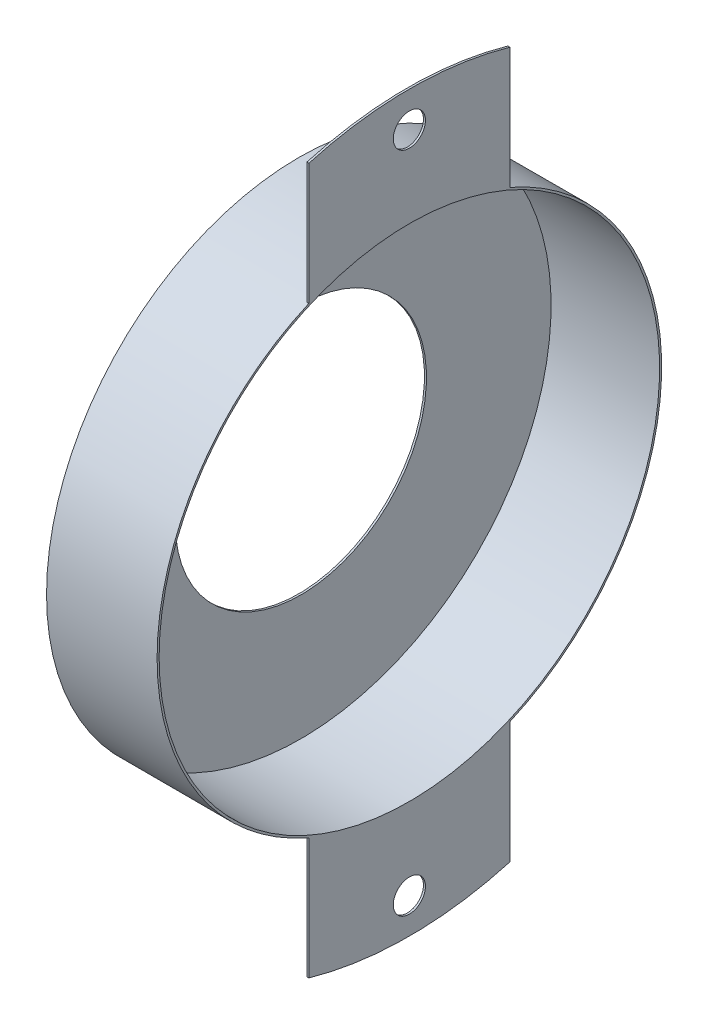
SolidWorks part; units mm, degrees
ref_plane "Ön Düzlem" through (0, 0, 0) normal (0, 0, 1) x (1, 0, 0)
ref_plane "Üst Düzlem" through (0, 0, 0) normal (0, 1, 0) x (1, 0, 0)
ref_plane "Sağ Düzlem" through (0, 0, 0) normal (1, 0, 0) x (0, 0, -1)
sketch "Sketch1" plane through (0, 0, 0) normal (0, 0, 1) x (1, 0, 0)
  line L0 (0, 0) -> (0, 25) construction
  line L1 (0, 25) -> (10.8, 25) construction
  line L2 (10.8, 25) -> (10.8, 36.5) construction
  line L3 (0, 0) -> (8.7607, 0) construction
  line L4 (0.1, 0) -> (0.1, 24.9)
  line L5 (0.1, 24.9) -> (10.9, 24.9)
  line L6 (10.9, 24.9) -> (10.9, 36.5)
  line L7 (-0.1, 0) -> (-0.1, 25.1)
  line L8 (-0.1, 25.1) -> (10.7, 25.1)
  line L9 (10.7, 25.1) -> (10.7, 36.5)
  line L10 (10.7, 36.5) -> (10.9, 36.5)
  line L11 (-0.1, 0) -> (0.1, 0)
  dimension "D1" = 25
  dimension "D2" = 10.8
  dimension "D3" = 11.5
  dimension "D4" = 0.1
  dimension "D5" = 0.1
revolve "Revolve1" add sketch "Sketch1" angle 360 about L3
sketch "Sketch2" plane through (-0.1, 0, 0) normal (-1, 0, 0) x (0, 0, 1)
  circle A0 centre (0, 0) radius 12.5
  dimension "D1" = 25
sketch "Sketch3" plane through (-0.1, 0, 0) normal (-1, 0, 0) x (0, 0, 1)
  line L0 (0, 36.5) -> (0, -36.5) construction
  line L1 (-10, 35.1034) -> (-10, -35.1034)
  line L2 (10, 35.1034) -> (10, -35.1034)
  line L3 (-10, 36.5) -> (-10, -36.5) construction
  line L4 (10, 36.5) -> (10, -36.5) construction
  circle A0 centre (0, 0) radius 36.5
  circle A1 centre (0, 0) radius 36.5 construction
  circle A2 centre (0, 0) radius 25.1
  circle M4 centre (0, 0) radius 25.1
  dimension "D3" = 50.2
  dimension "D1" = 10
  dimension "D2" = 10
extrude "Cut-Extrude2" cut sketch "Sketch3" against normal through all contours L1 A0 M4 | L2 A0 M4
sketch "Sketch4" plane through (10.7, 0, 0) normal (-1, 0, 0) x (0, 0, 1)
  circle A0 centre (0, 0) radius 33 construction
  circle A1 centre (0, 33) radius 1.6
  circle A2 centre (0, -33) radius 1.6
  dimension "D1" = 66
  dimension "D2" = 3.2
  dimension "D3" = 3.2
extrude "Cut-Extrude3" cut sketch "Sketch4" against normal through all contours A1 | A2
extrude "Cut-Extrude4" cut sketch "Sketch2" against normal blind 10
